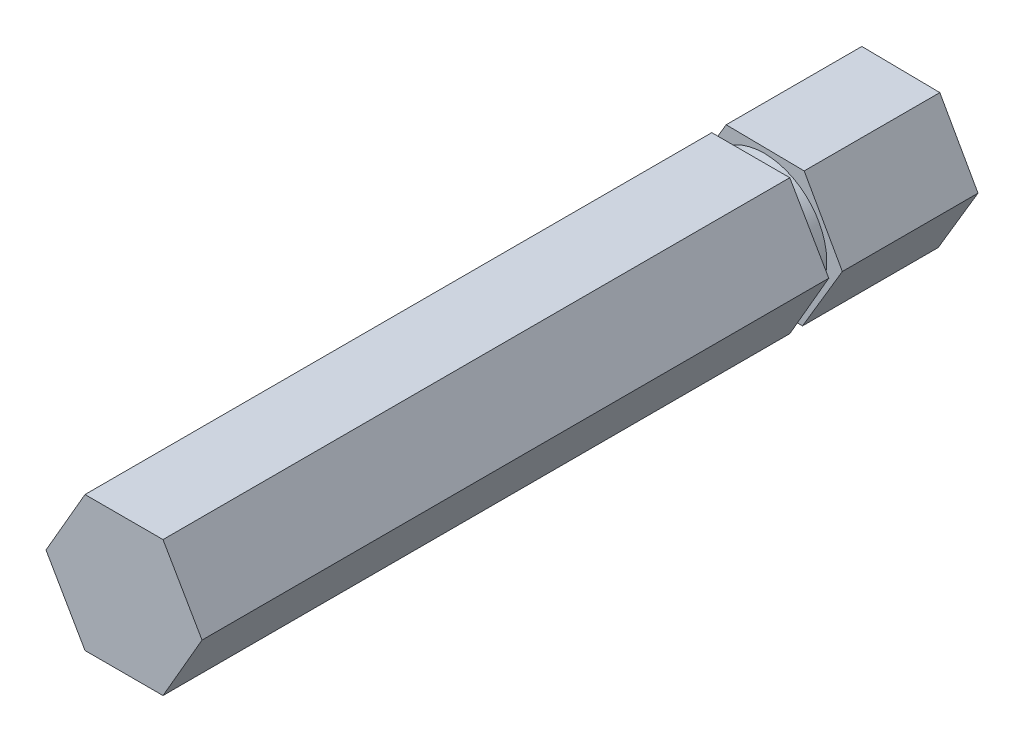
SolidWorks part; units mm, degrees
material "5052-H32"
ref_plane "Front Plane" through (0, 0, 0) normal (0, 0, 1) x (1, 0, 0)
ref_plane "Top Plane" through (0, 0, 0) normal (0, 1, 0) x (1, 0, 0)
ref_plane "Right Plane" through (0, 0, 0) normal (1, 0, 0) x (0, 0, -1)
sketch "Sketch 1" plane through (0, 0, 0) normal (0, 0, 1) x (1, 0, 0)
  line L1 (7.3025, 0) -> (3.6512, 6.3242)
  line L2 (3.6512, 6.3242) -> (-3.6512, 6.3242)
  line L3 (-3.6512, 6.3242) -> (-7.3025, 0)
  line L4 (-7.3025, 0) -> (-3.6513, -6.3242)
  line L5 (-3.6513, -6.3242) -> (3.6512, -6.3242)
  line L6 (3.6512, -6.3242) -> (7.3025, 0)
  circle A0 centre (0, 0) radius 6.3242 construction
  dimension "D1" = 7.3025
extrude "Boss-Extrude1" add sketch "Sketch 1" along normal mid plane 58.674
sketch "Sketch1" plane through (0, 0, -29.337) normal (0, 0, -1) x (-1, 0, 0)
  circle A0 centre (0, 0) radius 5.842
  dimension "D1" = 11.684
extrude "Boss-Extrude2" add sketch "Sketch1" along normal blind 1.27
sketch "Sketch2" plane through (0, 0, -30.607) normal (0, 0, -1) x (-1, 0, 0)
  line L0 (7.3025, 0) -> (3.6513, -6.3242) construction
  line L1 (3.7296, -6.2783) -> (7.3019, 0.0907)
  line L2 (7.3019, 0.0907) -> (3.5724, 6.369)
  line L3 (3.5724, 6.369) -> (-3.7296, 6.2783)
  line L4 (-3.7296, 6.2783) -> (-7.3019, -0.0907)
  line L5 (-7.3019, -0.0907) -> (-3.5724, -6.369)
  line L6 (-3.5724, -6.369) -> (3.7296, -6.2783)
  circle A0 centre (0, 0) radius 6.3242 construction
extrude "Boss-Extrude3" add sketch "Sketch2" along normal blind 12.7
